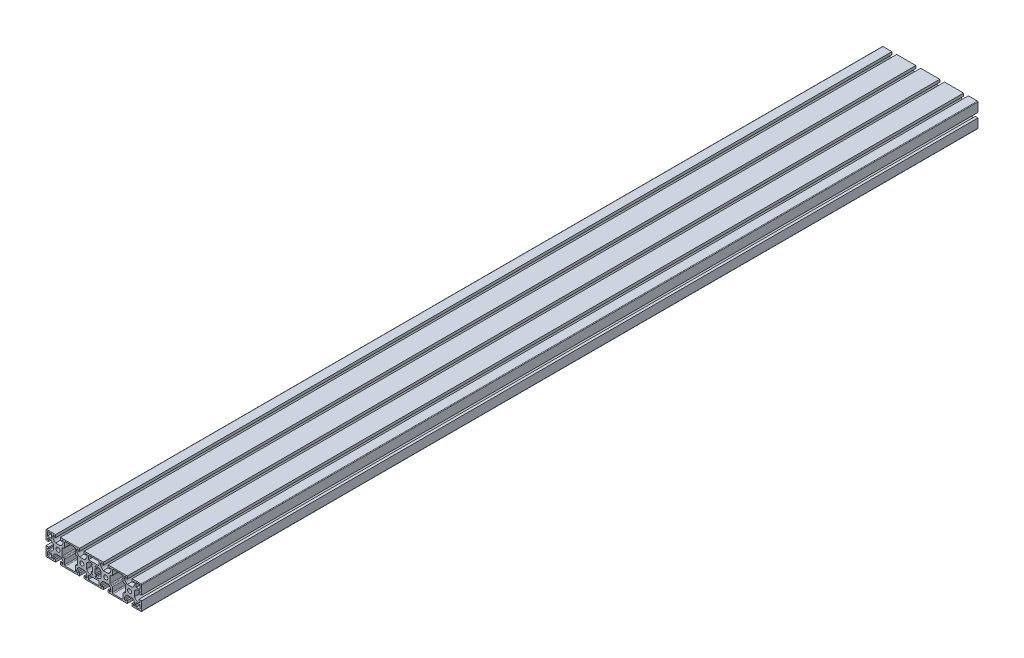
SolidWorks part; units mm, degrees
material "3.0255 (EN-AW 1350A)"
ref_plane "Płaszczyzna przednia" through (0, 0, 0) normal (0, 0, 1) x (1, 0, 0)
ref_plane "Płaszczyzna górna" through (0, 0, 0) normal (0, 1, 0) x (1, 0, 0)
ref_plane "Płaszczyzna prawa" through (0, 0, 0) normal (1, 0, 0) x (0, 0, -1)
sketch "Szkic1" plane through (0, 0, 0) normal (0, 0, 1) x (1, 0, 0)
  line L0 (0, 20) -> (0, -20) construction
  line L1 (-51.8865, 0) -> (40, 0) construction
  line L4 (-40, -20) -> (-40, 20)
  line L7 (-40, -20) -> (0, 0) construction
  line L8 (-40, 20) -> (40, -20) construction
  line L13 (20, 20) -> (20, 0) construction
  line L15 (24, 20) -> (24, 15.5)
  line L16 (24, 15.5) -> (26.4714, 15.5)
  line L21 (16, 15.5) -> (13.5286, 15.5)
  line L23 (16, 20) -> (13.5286, 20)
  line L24 (16, 20) -> (16, 15.5)
  line L25 (16, 7.75) -> (24, 7.75)
  line L26 (13.5286, 15.5) -> (13.5286, 17.75)
  line L27 (26.4714, 15.5) -> (26.4714, 17.75)
  line L28 (-24, 20) -> (-24, 15.5)
  line L29 (-26.4714, 15.5) -> (-26.4714, 17.75)
  line L30 (-24, 15.5) -> (-26.4714, 15.5)
  line L31 (-13.5286, 15.5) -> (-13.5286, 17.75)
  line L32 (-16, 15.5) -> (-13.5286, 15.5)
  line L33 (-16, 20) -> (-16, 15.5)
  line L34 (-16, 7.75) -> (-24, 7.75)
  line L35 (20, -20) -> (20, 0) construction
  line L36 (-40, -20) -> (0, 0) construction
  line L37 (-40, 20) -> (40, -20) construction
  line L38 (30.9714, -17.75) -> (36.75, -17.75)
  line L39 (-16, -7.75) -> (-24, -7.75)
  line L40 (-16, -20) -> (-16, -15.5)
  line L41 (-16, -15.5) -> (-13.5286, -15.5)
  line L42 (-13.5286, -15.5) -> (-13.5286, -17.75)
  line L43 (-24, -15.5) -> (-26.4714, -15.5)
  line L44 (-26.4714, -15.5) -> (-26.4714, -17.75)
  line L45 (-24, -20) -> (-24, -15.5)
  line L46 (26.4714, -15.5) -> (26.4714, -17.75)
  line L47 (13.5286, -15.5) -> (13.5286, -17.75)
  line L48 (16, -7.75) -> (24, -7.75)
  line L49 (16, -20) -> (16, -15.5)
  line L50 (16, -15.5) -> (13.5286, -15.5)
  line L51 (24, -15.5) -> (26.4714, -15.5)
  line L52 (24, -20) -> (24, -15.5)
  line L53 (40, -20) -> (0, 20) construction
  line L54 (35.5, 6.4714) -> (37.75, 6.4714)
  line L55 (35.5, 4) -> (35.5, 6.4714)
  line L56 (40, 4) -> (35.5, 4)
  line L57 (40, -4) -> (35.5, -4)
  line L58 (35.5, -4) -> (35.5, -6.4714)
  line L59 (35.5, -6.4714) -> (37.75, -6.4714)
  line L60 (27.75, 4) -> (27.75, -4)
  line L61 (-35.5, -6.4714) -> (-37.75, -6.4714)
  line L62 (-37.75, -4) -> (-35.5, -4)
  line L63 (-35.5, -4) -> (-35.5, -6.4714)
  line L64 (-35.5, 4) -> (-35.5, 6.4714)
  line L65 (-35.5, 6.4714) -> (-37.75, 6.4714)
  line L66 (-37.75, 4) -> (-35.5, 4)
  line L67 (-27.75, 4) -> (-27.75, -4)
  line L68 (-37.75, 4) -> (-37.75, -4)
  line L69 (40, -4) -> (40, -19)
  line L70 (40, 19) -> (40, 4)
  line L71 (-40, -20) -> (-24, -20)
  line L72 (-16, -20) -> (16, -20)
  line L73 (24, -20) -> (39, -20)
  line L74 (13.5286, 20) -> (-16, 20)
  line L75 (-24, 20) -> (-40, 20)
  line L76 (24, 20) -> (39, 20)
  line L77 (10.5286, 7.0902) -> (11.4095, 7.0902)
  line L78 (-7.5286, -17.75) -> (7.5286, -17.75)
  line L79 (-9.0286, -16.25) -> (-9.0286, -8.5902)
  line L80 (-7.5286, 17.75) -> (7.5286, 17.75)
  line L81 (9.0286, -16.25) -> (9.0286, -8.5902)
  line L82 (-9.0286, -17.75) -> (9.0286, 17.75) construction
  line L83 (-9.0286, 17.75) -> (9.0286, -17.75) construction
  line L84 (-11.4095, -7.0902) -> (-10.5286, -7.0902)
  line L85 (-12.9095, -5.5902) -> (-12.9095, 5.5902)
  line L86 (-11.4095, 7.0902) -> (-10.5286, 7.0902)
  line L87 (12.9095, -5.5902) -> (12.9095, 5.5902)
  line L88 (-12.9095, -7.0902) -> (0, 0) construction
  line L89 (-12.9095, 7.0902) -> (12.9095, -7.0902) construction
  line L90 (-9.0286, 8.5902) -> (-9.0286, 16.25)
  line L91 (-9.0286, 4.5143) -> (-9.0286, 4.9587)
  line L92 (-9.0286, -4.9587) -> (-9.0286, -4.5143)
  line L93 (9.0286, 8.5902) -> (9.0286, 16.25)
  line L94 (10.5286, -7.0902) -> (11.4095, -7.0902)
  line L96 (0, 0) -> (12.9095, 7.0902) construction
  line L98 (37.75, -10.9714) -> (37.75, -16.75)
  line L99 (30.9714, 10.9714) -> (37.75, 10.9714)
  line L100 (30.9714, 10.9714) -> (30.9714, 17.75)
  line L101 (30.9714, 17.75) -> (36.75, 17.75)
  line L102 (37.75, 10.9714) -> (37.75, 16.75)
  line L103 (30.9714, 10.9714) -> (37.75, 17.75) construction
  line L104 (30.9714, 17.75) -> (37.75, 10.9714) construction
  line L105 (30.9714, -10.9714) -> (37.75, -10.9714)
  line L106 (30.9714, -10.9714) -> (30.9714, -17.75)
  line L107 (-30.9714, -10.9714) -> (-30.9714, -17.75)
  line L108 (-30.9714, -10.9714) -> (-37.75, -10.9714)
  line L109 (-37.75, -10.9714) -> (-37.75, -16.75)
  line L110 (-30.9714, -17.75) -> (-36.75, -17.75)
  line L111 (-30.9714, 17.75) -> (-36.75, 17.75)
  line L112 (-37.75, 10.9714) -> (-37.75, 16.75)
  line L113 (-30.9714, 10.9714) -> (-37.75, 10.9714)
  line L114 (-30.9714, 10.9714) -> (-30.9714, 17.75)
  line L115 (-40, 52.1634) -> (-40, -64.8993) construction
  line L116 (-110.9714, 17.75) -> (-117.75, 10.9714) construction
  line L117 (-110.9714, 10.9714) -> (-117.75, 17.75) construction
  line L118 (-80, 0) -> (-92.9095, 7.0902) construction
  line L119 (-67.0905, 7.0902) -> (-92.9095, -7.0902) construction
  line L120 (-67.0905, -7.0902) -> (-80, 0) construction
  line L121 (-70.9714, 17.75) -> (-89.0286, -17.75) construction
  line L122 (-70.9714, -17.75) -> (-89.0286, 17.75) construction
  line L123 (-120, -20) -> (-80, 20) construction
  line L124 (-40, 20) -> (-120, -20) construction
  line L125 (-40, -20) -> (-80, 0) construction
  line L126 (-100, -20) -> (-100, 0) construction
  line L127 (-100, 20) -> (-100, 0) construction
  line L128 (-40, 20) -> (-120, -20) construction
  line L129 (-40, -20) -> (-80, 0) construction
  line L130 (-28.1135, 0) -> (-120, 0) construction
  line L131 (-80, 20) -> (-80, -20) construction
  line L132 (-49.0286, 10.9714) -> (-49.0286, 17.75)
  line L133 (-49.0286, 10.9714) -> (-42.25, 10.9714)
  line L134 (-42.25, 10.9714) -> (-42.25, 16.75)
  line L135 (-49.0286, 17.75) -> (-43.25, 17.75)
  line L136 (-49.0286, -17.75) -> (-43.25, -17.75)
  line L137 (-42.25, -10.9714) -> (-42.25, -16.75)
  line L138 (-49.0286, -10.9714) -> (-42.25, -10.9714)
  line L139 (-49.0286, -10.9714) -> (-49.0286, -17.75)
  line L140 (-110.9714, -10.9714) -> (-110.9714, -17.75)
  line L141 (-110.9714, -10.9714) -> (-117.75, -10.9714)
  line L142 (-117.75, 10.9714) -> (-117.75, 16.75)
  line L143 (-110.9714, 17.75) -> (-116.75, 17.75)
  line L144 (-110.9714, 10.9714) -> (-110.9714, 17.75)
  line L145 (-110.9714, 10.9714) -> (-117.75, 10.9714)
  line L146 (-117.75, -10.9714) -> (-117.75, -16.75)
  line L147 (-90.5286, -7.0902) -> (-91.4095, -7.0902)
  line L148 (-89.0286, 8.5902) -> (-89.0286, 16.25)
  line L149 (-70.9714, -4.9587) -> (-70.9714, -4.5143)
  line L150 (-70.9714, 4.5143) -> (-70.9714, 4.9587)
  line L151 (-70.9714, 8.5902) -> (-70.9714, 16.25)
  line L152 (-92.9095, -5.5902) -> (-92.9095, 5.5902)
  line L153 (-68.5905, 7.0902) -> (-69.4714, 7.0902)
  line L154 (-67.0905, -5.5902) -> (-67.0905, 5.5902)
  line L155 (-68.5905, -7.0902) -> (-69.4714, -7.0902)
  line L156 (-89.0286, -16.25) -> (-89.0286, -8.5902)
  line L157 (-72.4714, 17.75) -> (-87.5286, 17.75)
  line L158 (-70.9714, -16.25) -> (-70.9714, -8.5902)
  line L159 (-72.4714, -17.75) -> (-87.5286, -17.75)
  line L160 (-90.5286, 7.0902) -> (-91.4095, 7.0902)
  line L161 (-104, 20) -> (-119, 20)
  line L162 (-56, 20) -> (-40, 20)
  line L163 (-93.5286, 20) -> (-64, 20)
  line L164 (-104, -20) -> (-119, -20)
  line L165 (-64, -20) -> (-96, -20)
  line L166 (-40, -20) -> (-56, -20)
  line L167 (-120, 19) -> (-120, 4)
  line L168 (-120, -4) -> (-120, -19)
  line L169 (-42.25, 4) -> (-42.25, -4)
  line L170 (-52.25, 4) -> (-52.25, -4)
  line L171 (-42.25, 4) -> (-44.5, 4)
  line L172 (-44.5, 6.4714) -> (-42.25, 6.4714)
  line L173 (-44.5, 4) -> (-44.5, 6.4714)
  line L174 (-44.5, -4) -> (-44.5, -6.4714)
  line L175 (-42.25, -4) -> (-44.5, -4)
  line L176 (-44.5, -6.4714) -> (-42.25, -6.4714)
  line L177 (-107.75, 4) -> (-107.75, -4)
  line L178 (-115.5, -6.4714) -> (-117.75, -6.4714)
  line L179 (-115.5, -4) -> (-115.5, -6.4714)
  line L180 (-120, -4) -> (-115.5, -4)
  line L181 (-120, 4) -> (-115.5, 4)
  line L182 (-115.5, 4) -> (-115.5, 6.4714)
  line L183 (-115.5, 6.4714) -> (-117.75, 6.4714)
  line L184 (-104, -20) -> (-104, -15.5)
  line L185 (-104, -15.5) -> (-106.4714, -15.5)
  line L186 (-96, -15.5) -> (-93.5286, -15.5)
  line L187 (-96, -20) -> (-96, -15.5)
  line L188 (-96, -7.75) -> (-104, -7.75)
  line L189 (-93.5286, -15.5) -> (-93.5286, -17.75)
  line L190 (-106.4714, -15.5) -> (-106.4714, -17.75)
  line L191 (-56, -20) -> (-56, -15.5)
  line L192 (-53.5286, -15.5) -> (-53.5286, -17.75)
  line L193 (-56, -15.5) -> (-53.5286, -15.5)
  line L194 (-66.4714, -15.5) -> (-66.4714, -17.75)
  line L195 (-64, -15.5) -> (-66.4714, -15.5)
  line L196 (-64, -20) -> (-64, -15.5)
  line L197 (-64, -7.75) -> (-56, -7.75)
  line L198 (-110.9714, -17.75) -> (-116.75, -17.75)
  line L199 (-64, 7.75) -> (-56, 7.75)
  line L200 (-64, 20) -> (-64, 15.5)
  line L201 (-64, 15.5) -> (-66.4714, 15.5)
  line L202 (-66.4714, 15.5) -> (-66.4714, 17.75)
  line L203 (-56, 15.5) -> (-53.5286, 15.5)
  line L204 (-53.5286, 15.5) -> (-53.5286, 17.75)
  line L205 (-56, 20) -> (-56, 15.5)
  line L206 (-106.4714, 15.5) -> (-106.4714, 17.75)
  line L207 (-93.5286, 15.5) -> (-93.5286, 17.75)
  line L208 (-96, 7.75) -> (-104, 7.75)
  line L209 (-96, 20) -> (-96, 15.5)
  line L210 (-96, 20) -> (-93.5286, 20)
  line L211 (-96, 15.5) -> (-93.5286, 15.5)
  line L212 (-104, 15.5) -> (-106.4714, 15.5)
  line L213 (-104, 20) -> (-104, 15.5)
  line L215 (-43.25, 17.75) -> (-36.75, 17.75)
  line L216 (-42.25, 10.9714) -> (-37.75, 10.9714)
  line L217 (-42.25, -10.9714) -> (-37.75, -10.9714)
  line L218 (-43.25, -17.75) -> (-36.75, -17.75)
  circle A0 centre (-20, 0) radius 3.4
  circle A1 centre (20, 0) radius 3.4
  arc A2 (26.4714, 17.75) -> (28.7214, 15.5) centre (26.4714, 15.5) cw
  arc A3 (28.7214, 15.5) -> (24, 7.75) centre (20, 15.5) cw
  arc A4 (13.5286, 17.75) -> (11.2786, 15.5) centre (13.5286, 15.5) ccw
  arc A5 (11.2786, 15.5) -> (16, 7.75) centre (20, 15.5) ccw
  arc A6 (-26.4714, 17.75) -> (-28.7214, 15.5) centre (-26.4714, 15.5) ccw
  arc A7 (-13.5286, 17.75) -> (-11.2786, 15.5) centre (-13.5286, 15.5) cw
  arc A8 (-11.2786, 15.5) -> (-16, 7.75) centre (-20, 15.5) cw
  arc A9 (-28.7214, 15.5) -> (-24, 7.75) centre (-20, 15.5) ccw
  arc A10 (-28.7214, -15.5) -> (-24, -7.75) centre (-20, -15.5) cw
  arc A11 (-11.2786, -15.5) -> (-16, -7.75) centre (-20, -15.5) ccw
  arc A12 (-13.5286, -17.75) -> (-11.2786, -15.5) centre (-13.5286, -15.5) ccw
  arc A13 (-26.4714, -17.75) -> (-28.7214, -15.5) centre (-26.4714, -15.5) cw
  arc A14 (11.2786, -15.5) -> (16, -7.75) centre (20, -15.5) cw
  arc A15 (13.5286, -17.75) -> (11.2786, -15.5) centre (13.5286, -15.5) cw
  arc A16 (28.7214, -15.5) -> (24, -7.75) centre (20, -15.5) ccw
  arc A17 (26.4714, -17.75) -> (28.7214, -15.5) centre (26.4714, -15.5) ccw
  arc A18 (35.5, 8.7214) -> (27.75, 4) centre (35.5, 0) ccw
  arc A19 (37.75, 6.4714) -> (35.5, 8.7214) centre (35.5, 6.4714) ccw
  arc A20 (37.75, -6.4714) -> (35.5, -8.7214) centre (35.5, -6.4714) cw
  arc A21 (35.5, -8.7214) -> (27.75, -4) centre (35.5, 0) cw
  arc A22 (-35.5, -8.7214) -> (-27.75, -4) centre (-35.5, 0) ccw
  arc A23 (-37.75, -6.4714) -> (-35.5, -8.7214) centre (-35.5, -6.4714) ccw
  arc A24 (-37.75, 6.4714) -> (-35.5, 8.7214) centre (-35.5, 6.4714) cw
  arc A25 (-35.5, 8.7214) -> (-27.75, 4) centre (-35.5, 0) cw
  arc A26 (-10.5286, 7.0902) -> (-9.0286, 8.5902) centre (-10.5286, 8.5902) ccw
  arc A27 (-9.0286, -8.5902) -> (-10.5286, -7.0902) centre (-10.5286, -8.5902) ccw
  arc A28 (11.4095, -7.0902) -> (12.9095, -5.5902) centre (11.4095, -5.5902) ccw
  arc A29 (9.0286, -8.5902) -> (10.5286, -7.0902) centre (10.5286, -8.5902) cw
  arc A30 (7.5286, -17.75) -> (9.0286, -16.25) centre (7.5286, -16.25) ccw
  arc A31 (-7.5286, -17.75) -> (-9.0286, -16.25) centre (-7.5286, -16.25) cw
  arc A32 (-11.4095, -7.0902) -> (-12.9095, -5.5902) centre (-11.4095, -5.5902) cw
  arc A33 (-12.9095, 5.5902) -> (-11.4095, 7.0902) centre (-11.4095, 5.5902) cw
  arc A34 (-9.0286, 16.25) -> (-7.5286, 17.75) centre (-7.5286, 16.25) cw
  arc A35 (7.5286, 17.75) -> (9.0286, 16.25) centre (7.5286, 16.25) cw
  arc A36 (11.4095, 7.0902) -> (12.9095, 5.5902) centre (11.4095, 5.5902) cw
  arc A37 (10.5286, 7.0902) -> (9.0286, 8.5902) centre (10.5286, 8.5902) cw
  arc A40 (39, -20) -> (40, -19) centre (39, -19) ccw
  arc A41 (39, 20) -> (40, 19) centre (39, 19) cw
  arc A42 (36.75, 17.75) -> (37.75, 16.75) centre (36.75, 16.75) cw
  arc A43 (36.75, -17.75) -> (37.75, -16.75) centre (36.75, -16.75) ccw
  arc A44 (-36.75, -17.75) -> (-37.75, -16.75) centre (-36.75, -16.75) cw
  arc A45 (-36.75, 17.75) -> (-37.75, 16.75) centre (-36.75, 16.75) ccw
  arc A46 (-43.25, 17.75) -> (-42.25, 16.75) centre (-43.25, 16.75) cw
  arc A47 (-43.25, -17.75) -> (-42.25, -16.75) centre (-43.25, -16.75) ccw
  arc A48 (-116.75, -17.75) -> (-117.75, -16.75) centre (-116.75, -16.75) cw
  arc A49 (-116.75, 17.75) -> (-117.75, 16.75) centre (-116.75, 16.75) ccw
  arc A50 (-119, 20) -> (-120, 19) centre (-119, 19) ccw
  arc A51 (-119, -20) -> (-120, -19) centre (-119, -19) cw
  arc A54 (-90.5286, 7.0902) -> (-89.0286, 8.5902) centre (-90.5286, 8.5902) ccw
  arc A55 (-91.4095, 7.0902) -> (-92.9095, 5.5902) centre (-91.4095, 5.5902) ccw
  arc A56 (-87.5286, 17.75) -> (-89.0286, 16.25) centre (-87.5286, 16.25) ccw
  arc A57 (-70.9714, 16.25) -> (-72.4714, 17.75) centre (-72.4714, 16.25) ccw
  arc A58 (-67.0905, 5.5902) -> (-68.5905, 7.0902) centre (-68.5905, 5.5902) ccw
  arc A59 (-68.5905, -7.0902) -> (-67.0905, -5.5902) centre (-68.5905, -5.5902) ccw
  arc A60 (-72.4714, -17.75) -> (-70.9714, -16.25) centre (-72.4714, -16.25) ccw
  arc A61 (-87.5286, -17.75) -> (-89.0286, -16.25) centre (-87.5286, -16.25) cw
  arc A62 (-89.0286, -8.5902) -> (-90.5286, -7.0902) centre (-90.5286, -8.5902) ccw
  arc A63 (-91.4095, -7.0902) -> (-92.9095, -5.5902) centre (-91.4095, -5.5902) cw
  arc A64 (-70.9714, -8.5902) -> (-69.4714, -7.0902) centre (-69.4714, -8.5902) cw
  arc A65 (-69.4714, 7.0902) -> (-70.9714, 8.5902) centre (-69.4714, 8.5902) cw
  arc A66 (-44.5, 8.7214) -> (-52.25, 4) centre (-44.5, 0) ccw
  arc A67 (-42.25, 6.4714) -> (-44.5, 8.7214) centre (-44.5, 6.4714) ccw
  arc A68 (-42.25, -6.4714) -> (-44.5, -8.7214) centre (-44.5, -6.4714) cw
  arc A69 (-44.5, -8.7214) -> (-52.25, -4) centre (-44.5, 0) cw
  arc A70 (-115.5, -8.7214) -> (-107.75, -4) centre (-115.5, 0) ccw
  arc A71 (-117.75, -6.4714) -> (-115.5, -8.7214) centre (-115.5, -6.4714) ccw
  arc A72 (-117.75, 6.4714) -> (-115.5, 8.7214) centre (-115.5, 6.4714) cw
  arc A73 (-115.5, 8.7214) -> (-107.75, 4) centre (-115.5, 0) cw
  arc A74 (-106.4714, -17.75) -> (-108.7214, -15.5) centre (-106.4714, -15.5) cw
  arc A75 (-108.7214, -15.5) -> (-104, -7.75) centre (-100, -15.5) cw
  arc A76 (-93.5286, -17.75) -> (-91.2786, -15.5) centre (-93.5286, -15.5) ccw
  arc A77 (-91.2786, -15.5) -> (-96, -7.75) centre (-100, -15.5) ccw
  arc A78 (-53.5286, -17.75) -> (-51.2786, -15.5) centre (-53.5286, -15.5) ccw
  arc A79 (-66.4714, -17.75) -> (-68.7214, -15.5) centre (-66.4714, -15.5) cw
  arc A80 (-68.7214, -15.5) -> (-64, -7.75) centre (-60, -15.5) cw
  arc A81 (-51.2786, -15.5) -> (-56, -7.75) centre (-60, -15.5) ccw
  arc A82 (-51.2786, 15.5) -> (-56, 7.75) centre (-60, 15.5) cw
  arc A83 (-68.7214, 15.5) -> (-64, 7.75) centre (-60, 15.5) ccw
  arc A84 (-66.4714, 17.75) -> (-68.7214, 15.5) centre (-66.4714, 15.5) ccw
  arc A85 (-53.5286, 17.75) -> (-51.2786, 15.5) centre (-53.5286, 15.5) cw
  arc A86 (-91.2786, 15.5) -> (-96, 7.75) centre (-100, 15.5) cw
  arc A87 (-93.5286, 17.75) -> (-91.2786, 15.5) centre (-93.5286, 15.5) cw
  arc A88 (-108.7214, 15.5) -> (-104, 7.75) centre (-100, 15.5) ccw
  arc A89 (-106.4714, 17.75) -> (-108.7214, 15.5) centre (-106.4714, 15.5) ccw
  circle A90 centre (-100, 0) radius 3.4
  circle A91 centre (-60, 0) radius 3.4
  point P0 (-40, -19.1761)
  point P5 (0, 0)
  point P16 (0, 0)
  point P17 (0, 0)
  point P30 (24, 17.75)
  point P108 (0, 0)
  point P124 (-9.0286, 7.0902)
  point P132 (9.0286, -7.0902)
  point P156 (9.0286, 7.0902)
  point P161 (40, 20)
  point P162 (34.3607, 14.3607)
  point P364 (-114.3607, 14.3607)
  point P365 (-120, 20)
  point P366 (-89.0286, 7.0902)
  point P367 (-89.0286, -7.0902)
  point P368 (-70.9714, 7.0902)
  point P369 (-80, 0)
  point P370 (-80, 0)
  point P371 (-80, 0)
  dimension "D4" = 6.8
  dimension "D5" = 12.25
  dimension "D9" = 11
  dimension "D11" = 1.5
  dimension "D16" = 1
  dimension "D1" = 80
  dimension "D2" = 40
  dimension "D3" = 40
  dimension "D6" = 2.25
  dimension "D7" = 8
  dimension "D8" = 4.5
  dimension "D10" = 14.1804
  dimension "D13" = 2.25
  dimension "D14" = 2.25
  dimension "D15" = 2.25
extrude "Dodanie-wyciągnięcie1" add sketch "Szkic1" along normal blind 1400
